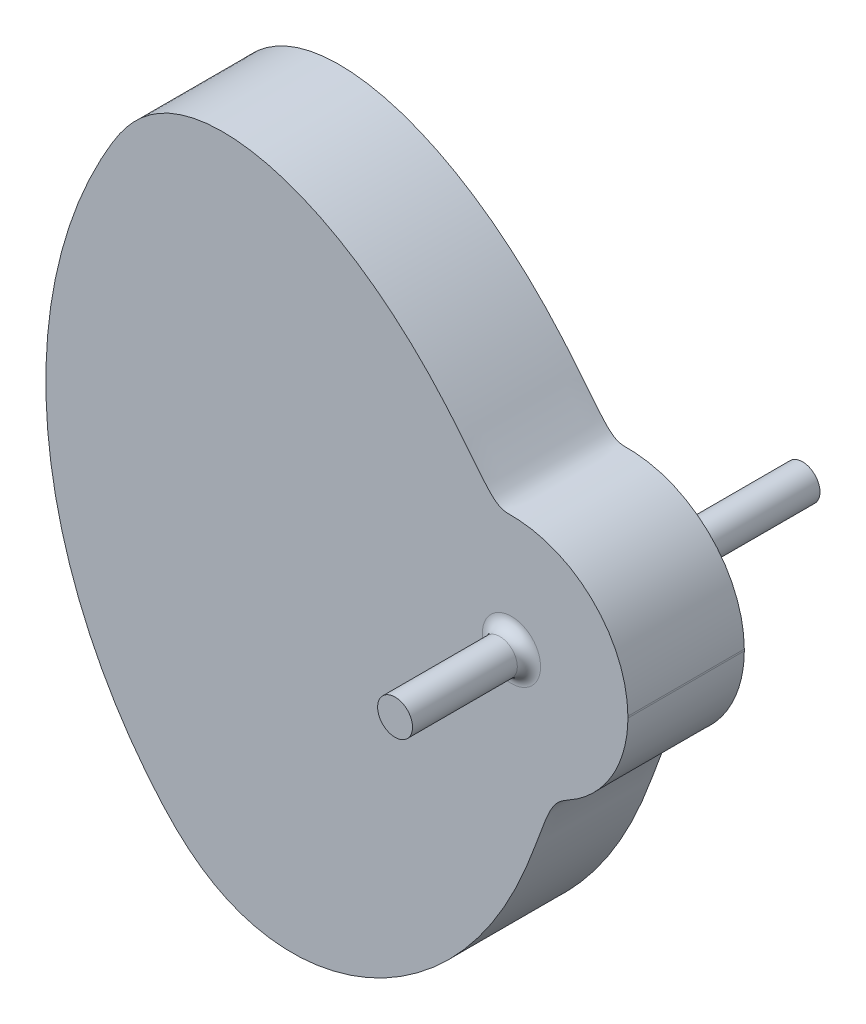
SolidWorks part; units mm, degrees
ref_plane "Front Plane" through (0, 0, 0) normal (0, 0, 1) x (1, 0, 0)
ref_plane "Top Plane" through (0, 0, 0) normal (0, 1, 0) x (1, 0, 0)
ref_plane "Right Plane" through (0, 0, 0) normal (1, 0, 0) x (0, 0, -1)
curve "Curve8"
  spline degree 3 poles (25.4, 0, 0) (25.3998, 0.0847, 0) (25.3993, 0.254, 0) (25.3953, 0.508, 0) (25.389, 0.7619, 0) (25.3801, 1.0157, 0) (25.3687, 1.2695, 0) (25.3547, 1.5231, 0) (25.3382, 1.7766, 0) (25.3192, 2.0299, 0) (25.2976, 2.283, 0) (25.2735, 2.5358, 0) (25.2469, 2.7884, 0) (25.2178, 3.0407, 0) (25.1861, 3.2928, 0) (25.1519, 3.5445, 0) (25.1152, 3.7958, 0) (25.076, 4.0467, 0) (25.0343, 4.2973, 0) (24.99, 4.5474, 0) (24.9433, 4.7971, 0) (24.8941, 5.0463, 0) (24.8424, 5.295, 0) (24.7882, 5.5431, 0) (24.7315, 5.7907, 0) (24.6724, 6.0377, 0) (24.6108, 6.2842, 0) (24.5467, 6.53, 0) (24.4802, 6.7751, 0) (24.4112, 7.0196, 0) (24.3398, 7.2633, 0) (24.266, 7.5063, 0) (24.1897, 7.7486, 0) (24.111, 7.9901, 0) (24.0299, 8.2308, 0) (23.9464, 8.4707, 0) (23.8605, 8.7097, 0) (23.7722, 8.9479, 0) (23.6815, 9.1852, 0) (23.5885, 9.4215, 0) (23.4931, 9.6569, 0) (23.3953, 9.8914, 0) (23.2953, 10.1248, 0) (23.1928, 10.3573, 0) (23.0881, 10.5887, 0) (22.9811, 10.819, 0) (22.8717, 11.0483, 0) (22.7601, 11.2765, 0) (22.6462, 11.5035, 0) (22.53, 11.7294, 0) (22.4116, 11.9541, 0) (22.291, 12.1776, 0) (22.1681, 12.3999, 0) (22.043, 12.621, 0) (21.9157, 12.8408, 0) (21.7862, 13.0593, 0) (21.6545, 13.2765, 0) (21.5206, 13.4924, 0) (21.3846, 13.7069, 0) (21.2465, 13.92, 0) (21.1062, 14.1318, 0) (20.9639, 14.3422, 0) (20.8194, 14.5511, 0) (20.6729, 14.7585, 0) (20.5242, 14.9645, 0) (20.3736, 15.169, 0) (20.2209, 15.372, 0) (20.0661, 15.5734, 0) (19.9094, 15.7733, 0) (19.7507, 15.9716, 0) (19.59, 16.1683, 0) (19.4273, 16.3634, 0) (19.2627, 16.5569, 0) (19.0962, 16.7486, 0) (18.9277, 16.9388, 0) (18.7574, 17.1272, 0) (18.5852, 17.3139, 0) (18.4111, 17.4989, 0) (18.2352, 17.6821, 0) (18.0575, 17.8636, 0) (17.878, 18.0433, 0) (17.6966, 18.2211, 0) (17.5136, 18.3972, 0) (17.3287, 18.5714, 0) (17.1421, 18.7438, 0) (16.9538, 18.9143, 0) (16.7639, 19.0828, 0) (16.5722, 19.2495, 0) (16.3789, 19.4143, 0) (16.1839, 19.5771, 0) (15.9873, 19.738, 0) (15.7892, 19.8968, 0) (15.5894, 20.0537, 0) (15.3881, 20.2086, 0) (15.1852, 20.3615, 0) (14.9809, 20.5123, 0) (14.775, 20.6611, 0) (14.5677, 20.8078, 0) (14.3588, 20.9524, 0) (14.1486, 21.095, 0) (13.937, 21.2354, 0) (13.7239, 21.3737, 0) (13.5095, 21.5099, 0) (13.2937, 21.6439, 0) (13.0766, 21.7758, 0) (12.8582, 21.9054, 0) (12.6385, 22.0329, 0) (12.4176, 22.1582, 0) (12.1954, 22.2813, 0) (11.9719, 22.4021, 0) (11.7473, 22.5207, 0) (11.5215, 22.637, 0) (11.2946, 22.7511, 0) (11.0665, 22.8629, 0) (10.8373, 22.9725, 0) (10.6071, 23.0797, 0) (10.3758, 23.1846, 0) (10.1434, 23.2872, 0) (9.91, 23.3875, 0) (9.6757, 23.4854, 0) (9.4403, 23.581, 0) (9.204, 23.6742, 0) (8.9668, 23.765, 0) (8.7287, 23.8535, 0) (8.4898, 23.9396, 0) (8.25, 24.0233, 0) (8.0093, 24.1046, 0) (7.7679, 24.1835, 0) (7.5257, 24.26, 0) (7.2827, 24.334, 0) (7.039, 24.4056, 0) (6.7946, 24.4748, 0) (6.5495, 24.5415, 0) (6.3038, 24.6058, 0) (6.0574, 24.6676, 0) (5.8104, 24.7269, 0) (5.5629, 24.7838, 0) (5.3148, 24.8382, 0) (5.0661, 24.8901, 0) (4.817, 24.9395, 0) (4.5673, 24.9864, 0) (4.3172, 25.0308, 0) (4.0667, 25.0728, 0) (3.8158, 25.1122, 0) (3.5645, 25.1491, 0) (3.3128, 25.1835, 0) (3.0608, 25.2153, 0) (2.8085, 25.2447, 0) (2.5559, 25.2715, 0) (2.3031, 25.2958, 0) (2.05, 25.3176, 0) (1.7968, 25.3368, 0) (1.5433, 25.3535, 0) (1.2897, 25.3677, 0) (1.036, 25.3793, 0) (0.7821, 25.3884, 0) (0.5282, 25.3949, 0) (0.2742, 25.3989, 0) (0.0982, 25.4, 0) (-0.0779, 25.4, 0) (-0.254, 25.3992, 0) (-0.5082, 25.3992, 0) (-0.7628, 25.4043, 0) (-1.0181, 25.4179, 0) (-1.2748, 25.4431, 0) (-1.5333, 25.4829, 0) (-1.7942, 25.5403, 0) (-2.0584, 25.6178, 0) (-2.3265, 25.7176, 0) (-2.5995, 25.8418, 0) (-2.8782, 25.9922, 0) (-3.1636, 26.1705, 0) (-3.457, 26.3779, 0) (-3.7593, 26.6159, 0) (-4.0719, 26.8853, 0) (-4.396, 27.187, 0) (-4.7327, 27.5217, 0) (-5.0833, 27.89, 0) (-5.449, 28.292, 0) (-5.831, 28.7281, 0) (-6.2306, 29.1981, 0) (-6.6488, 29.7019, 0) (-7.0868, 30.2392, 0) (-7.5457, 30.8095, 0) (-8.0266, 31.4122, 0) (-8.5304, 32.0464, 0) (-9.0582, 32.7113, 0) (-9.6107, 33.4058, 0) (-10.1889, 34.1289, 0) (-10.7934, 34.8791, 0) (-11.4251, 35.6552, 0) (-12.0844, 36.4557, 0) (-12.772, 37.279, 0) (-13.4884, 38.1234, 0) (-14.2338, 38.9872, 0) (-15.0087, 39.8685, 0) (-15.8131, 40.7655, 0) (-16.6474, 41.6762, 0) (-17.5114, 42.5986, 0) (-18.4052, 43.5307, 0) (-19.3286, 44.4704, 0) (-20.2813, 45.4154, 0) (-21.2631, 46.3638, 0) (-22.2735, 47.3132, 0) (-23.312, 48.2616, 0) (-24.378, 49.2067, 0) (-25.4708, 50.1462, 0) (-26.5897, 51.0781, 0) (-27.7337, 52.0001, 0) (-28.902, 52.9101, 0) (-30.0935, 53.8059, 0) (-31.307, 54.6853, 0) (-32.5415, 55.5464, 0) (-33.7956, 56.3871, 0) (-35.0679, 57.2054, 0) (-36.3572, 57.9993, 0) (-37.6619, 58.767, 0) (-38.9805, 59.5066, 0) (-40.3115, 60.2164, 0) (-41.6531, 60.8947, 0) (-43.0037, 61.54, 0) (-44.3617, 62.1506, 0) (-45.7252, 62.7251, 0) (-47.0924, 63.2622, 0) (-48.4616, 63.7607, 0) (-49.8308, 64.2193, 0) (-51.1984, 64.637, 0) (-52.5624, 65.0128, 0) (-53.9209, 65.3459, 0) (-55.2721, 65.6354, 0) (-56.6142, 65.8808, 0) (-57.9454, 66.0815, 0) (-59.2638, 66.2371, 0) (-60.5677, 66.3473, 0) (-61.8554, 66.4117, 0) (-63.1252, 66.4305, 0) (-64.3755, 66.4035, 0) (-65.6047, 66.3309, 0) (-66.8114, 66.2131, 0) (-67.9941, 66.0502, 0) (-69.1514, 65.8429, 0) (-70.2822, 65.5917, 0) (-71.3853, 65.2973, 0) (-72.4597, 64.9606, 0) (-73.5044, 64.5824, 0) (-74.5187, 64.1639, 0) (-75.5019, 63.706, 0) (-76.4534, 63.2101, 0) (-77.3729, 62.6775, 0) (-78.2602, 62.1097, 0) (-79.1152, 61.5081, 0) (-79.9381, 60.8743, 0) (-80.7291, 60.2101, 0) (-81.4888, 59.5171, 0) (-82.2178, 58.7973, 0) (-82.9171, 58.0524, 0) (-83.5877, 57.2844, 0) (-84.231, 56.4954, 0) (-84.8486, 55.6873, 0) (-85.4422, 54.8621, 0) (-86.014, 54.022, 0) (-86.5661, 53.1691, 0) (-87.1011, 52.3053, 0) (-87.5733, 51.5144, 0) (-88.0367, 50.7184, 0) (-88.4932, 49.9184, 0) (-88.988, 49.031, 0) (-89.4739, 48.1387, 0) (-89.9508, 47.2416, 0) (-90.4187, 46.3397, 0) (-90.8775, 45.4332, 0) (-91.3273, 44.5222, 0) (-91.768, 43.6067, 0) (-92.1994, 42.6869, 0) (-92.6217, 41.7627, 0) (-93.0347, 40.8345, 0) (-93.4384, 39.9021, 0) (-93.8327, 38.9657, 0) (-94.2177, 38.0255, 0) (-94.5932, 37.0814, 0) (-94.9593, 36.1336, 0) (-95.3159, 35.1822, 0) (-95.6629, 34.2273, 0) (-96.0004, 33.269, 0) (-96.3283, 32.3074, 0) (-96.6465, 31.3425, 0) (-96.9551, 30.3745, 0) (-97.254, 29.4034, 0) (-97.5432, 28.4294, 0) (-97.8226, 27.4526, 0) (-98.0922, 26.473, 0) (-98.352, 25.4908, 0) (-98.602, 24.506, 0) (-98.8422, 23.5188, 0) (-99.0724, 22.5292, 0) (-99.2927, 21.5373, 0) (-99.5031, 20.5434, 0) (-99.7036, 19.5473, 0) (-99.8941, 18.5493, 0) (-100.0746, 17.5495, 0) (-100.2451, 16.5479, 0) (-100.4055, 15.5446, 0) (-100.5559, 14.5398, 0) (-100.6963, 13.5335, 0) (-100.8266, 12.5259, 0) (-100.9468, 11.517, 0) (-101.057, 10.507, 0) (-101.157, 9.4959, 0) (-101.2469, 8.4839, 0) (-101.3266, 7.471, 0) (-101.3963, 6.4574, 0) (-101.4558, 5.4431, 0) (-101.5051, 4.4283, 0) (-101.5444, 3.4131, 0) (-101.5734, 2.3975, 0) (-101.5923, 1.3816, 0) (-101.601, 0.3656, 0) (-101.5996, -0.6504, 0) (-101.588, -1.6663, 0) (-101.5663, -2.6821, 0) (-101.5344, -3.6976, 0) (-101.4923, -4.7128, 0) (-101.4401, -5.7274, 0) (-101.3778, -6.7415, 0) (-101.3053, -7.7549, 0) (-101.2227, -8.7676, 0) (-101.13, -9.7794, 0) (-101.0271, -10.7902, 0) (-100.9142, -11.7999, 0) (-100.7911, -12.8084, 0) (-100.658, -13.8157, 0) (-100.5148, -14.8215, 0) (-100.3616, -15.8259, 0) (-100.1983, -16.8287, 0) (-100.025, -17.8299, 0) (-99.8417, -18.8292, 0) (-99.6484, -19.8267, 0) (-99.4452, -20.8221, 0) (-99.232, -21.8155, 0) (-99.0089, -22.8067, 0) (-98.7759, -23.7957, 0) (-98.533, -24.7822, 0) (-98.2802, -25.7663, 0) (-98.0176, -26.7478, 0) (-97.7453, -27.7266, 0) (-97.4631, -28.7027, 0) (-97.1712, -29.6758, 0) (-96.8696, -30.6461, 0) (-96.5583, -31.6132, 0) (-96.2374, -32.5772, 0) (-95.9068, -33.5379, 0) (-95.5666, -34.4953, 0) (-95.2169, -35.4492, 0) (-94.8576, -36.3996, 0) (-94.4889, -37.3463, 0) (-94.1107, -38.2894, 0) (-93.7231, -39.2285, 0) (-93.3262, -40.1638, 0) (-92.9199, -41.095, 0) (-92.5043, -42.0222, 0) (-92.0794, -42.9451, 0) (-91.6454, -43.8637, 0) (-91.2022, -44.778, 0) (-90.7499, -45.6877, 0) (-90.2884, -46.5929, 0) (-89.818, -47.4935, 0) (-89.3386, -48.3893, 0) (-88.8502, -49.2802, 0) (-88.353, -50.1662, 0) (-87.8469, -51.0472, 0) (-87.3321, -51.9231, 0) (-86.8085, -52.7938, 0) (-86.2762, -53.6593, 0) (-85.7353, -54.5193, 0) (-85.1859, -55.374, 0) (-84.6279, -56.223, 0) (-84.0614, -57.0665, 0) (-83.4866, -57.9042, 0) (-82.9033, -58.7362, 0) (-82.3118, -59.5623, 0) (-81.7121, -60.3824, 0) (-81.1042, -61.1965, 0) (-80.4882, -62.0045, 0) (-79.8642, -62.8062, 0) (-79.2321, -63.6017, 0) (-78.5921, -64.3908, 0) (-78.1229, -64.9578, 0) (-77.6503, -65.5219, 0) (-77.1744, -66.0833, 0) (-76.5085, -66.8507, 0) (-75.8326, -67.6092, 0) (-75.1456, -68.3577, 0) (-74.4467, -69.095, 0) (-73.7351, -69.82, 0) (-73.0101, -70.5316, 0) (-72.2711, -71.2286, 0) (-71.5175, -71.9099, 0) (-70.7489, -72.5745, 0) (-69.9649, -73.2213, 0) (-69.1653, -73.8492, 0) (-68.3497, -74.4571, 0) (-67.5182, -75.0442, 0) (-66.6705, -75.6094, 0) (-65.8067, -76.1519, 0) (-64.9269, -76.6706, 0) (-64.0312, -77.1648, 0) (-63.1197, -77.6335, 0) (-62.1928, -78.0761, 0) (-61.2507, -78.4917, 0) (-60.2938, -78.8796, 0) (-59.3225, -79.2392, 0) (-58.3373, -79.5698, 0) (-57.3386, -79.8709, 0) (-56.327, -80.1418, 0) (-55.3031, -80.3822, 0) (-54.2676, -80.5915, 0) (-53.221, -80.7694, 0) (-52.1641, -80.9154, 0) (-51.0976, -81.0294, 0) (-50.0222, -81.1109, 0) (-48.9388, -81.1599, 0) (-47.8481, -81.1761, 0) (-46.751, -81.1595, 0) (-45.6482, -81.11, 0) (-44.5407, -81.0275, 0) (-43.4293, -80.9121, 0) (-42.3148, -80.7639, 0) (-41.1983, -80.583, 0) (-40.0804, -80.3696, 0) (-38.9623, -80.1239, 0) (-37.8447, -79.8462, 0) (-36.7285, -79.5368, 0) (-35.6147, -79.196, 0) (-34.5042, -78.8244, 0) (-33.3977, -78.4222, 0) (-32.2962, -77.9901, 0) (-31.2006, -77.5286, 0) (-30.1117, -77.0382, 0) (-29.0303, -76.5195, 0) (-27.9573, -75.9733, 0) (-26.8935, -75.4002, 0) (-25.8396, -74.8009, 0) (-24.7964, -74.1762, 0) (-23.7647, -73.527, 0) (-22.7452, -72.854, 0) (-21.7386, -72.1581, 0) (-20.7454, -71.4402, 0) (-19.7665, -70.7012, 0) (-18.8024, -69.9421, 0) (-17.8536, -69.1638, 0) (-16.9207, -68.3673, 0) (-16.0043, -67.5537, 0) (-15.1048, -66.724, 0) (-14.2227, -65.8792, 0) (-13.3583, -65.0205, 0) (-12.5121, -64.1488, 0) (-11.6845, -63.2653, 0) (-10.8756, -62.3711, 0) (-10.0859, -61.4673, 0) (-9.3154, -60.5551, 0) (-8.5646, -59.6355, 0) (-7.8334, -58.7097, 0) (-7.122, -57.7788, 0) (-6.4305, -56.8439, 0) (-5.759, -55.9063, 0) (-5.1074, -54.9669, 0) (-4.4758, -54.0269, 0) (-3.864, -53.0875, 0) (-3.272, -52.1497, 0) (-2.6996, -51.2146, 0) (-2.1467, -50.2833, 0) (-1.613, -49.3568, 0) (-1.0984, -48.4361, 0) (-0.6024, -47.5224, 0) (-0.1249, -46.6165, 0) (0.3345, -45.7194, 0) (0.7762, -44.8322, 0) (1.2007, -43.9557, 0) (1.6082, -43.0907, 0) (1.9994, -42.2382, 0) (2.3746, -41.399, 0) (2.7344, -40.5739, 0) (3.0793, -39.7636, 0) (3.4099, -38.9688, 0) (3.7267, -38.1903, 0) (4.0304, -37.4287, 0) (4.3216, -36.6846, 0) (4.6009, -35.9584, 0) (4.8689, -35.2509, 0) (5.1263, -34.5623, 0) (5.3737, -33.8932, 0) (5.6119, -33.2439, 0) (5.8415, -32.6148, 0) (6.0632, -32.0061, 0) (6.2776, -31.418, 0) (6.4855, -30.8508, 0) (6.6876, -30.3045, 0) (6.8845, -29.7793, 0) (7.0768, -29.2751, 0) (7.2653, -28.7918, 0) (7.4506, -28.3295, 0) (7.6332, -27.888, 0) (7.8139, -27.4671, 0) (7.9933, -27.0664, 0) (8.1718, -26.6858, 0) (8.35, -26.3248, 0) (8.5285, -25.9831, 0) (8.7077, -25.66, 0) (8.8881, -25.3553, 0) (9.0701, -25.0681, 0) (9.254, -24.798, 0) (9.4403, -24.5442, 0) (9.6291, -24.3061, 0) (9.8207, -24.0827, 0) (10.0154, -23.8733, 0) (10.2131, -23.677, 0) (10.414, -23.4928, 0) (10.618, -23.3198, 0) (10.8251, -23.1569, 0) (11.0352, -23.003, 0) (11.248, -22.857, 0) (11.4632, -22.7176, 0) (11.6807, -22.5837, 0) (11.8998, -22.454, 0) (12.1201, -22.3271, 0) (12.3411, -22.2017, 0) (12.5346, -22.092, 0) (12.7275, -21.9815, 0) (12.9195, -21.8693, 0) (13.1376, -21.739, 0) (13.3543, -21.6066, 0) (13.5697, -21.4719, 0) (13.7838, -21.3352, 0) (13.9964, -21.1963, 0) (14.2077, -21.0553, 0) (14.4175, -20.9121, 0) (14.6259, -20.7669, 0) (14.8328, -20.6196, 0) (15.0383, -20.4703, 0) (15.2422, -20.3189, 0) (15.4447, -20.1654, 0) (15.6455, -20.01, 0) (15.8449, -19.8525, 0) (16.0426, -19.6931, 0) (16.2387, -19.5317, 0) (16.4332, -19.3683, 0) (16.6261, -19.203, 0) (16.8173, -19.0358, 0) (17.0068, -18.8667, 0) (17.1946, -18.6957, 0) (17.3807, -18.5228, 0) (17.565, -18.348, 0) (17.7476, -18.1715, 0) (17.9285, -17.9931, 0) (18.1075, -17.8129, 0) (18.2847, -17.631, 0) (18.4601, -17.4472, 0) (18.6337, -17.2618, 0) (18.8053, -17.0746, 0) (18.9751, -16.8857, 0) (19.143, -16.6951, 0) (19.309, -16.5028, 0) (19.4731, -16.3089, 0) (19.6352, -16.1134, 0) (19.7954, -15.9162, 0) (19.9535, -15.7175, 0) (20.1097, -15.5171, 0) (20.2639, -15.3153, 0) (20.416, -15.1119, 0) (20.5661, -14.9069, 0) (20.7141, -14.7005, 0) (20.8601, -14.4927, 0) (21.004, -14.2834, 0) (21.1458, -14.0726, 0) (21.2854, -13.8604, 0) (21.423, -13.6469, 0) (21.5584, -13.432, 0) (21.6916, -13.2157, 0) (21.8227, -12.9982, 0) (21.9516, -12.7793, 0) (22.0783, -12.5591, 0) (22.2027, -12.3377, 0) (22.325, -12.1151, 0) (22.445, -11.8912, 0) (22.5628, -11.6662, 0) (22.6784, -11.44, 0) (22.7916, -11.2126, 0) (22.9026, -10.9842, 0) (23.0113, -10.7546, 0) (23.1177, -10.524, 0) (23.2218, -10.2923, 0) (23.3235, -10.0595, 0) (23.423, -9.8258, 0) (23.5201, -9.5911, 0) (23.6148, -9.3554, 0) (23.7072, -9.1188, 0) (23.7972, -8.8813, 0) (23.8848, -8.6428, 0) (23.97, -8.4036, 0) (24.0528, -8.1635, 0) (24.1333, -7.9225, 0) (24.2113, -7.6808, 0) (24.2869, -7.4383, 0) (24.3601, -7.1951, 0) (24.4308, -6.9511, 0) (24.4991, -6.7065, 0) (24.5649, -6.4611, 0) (24.6283, -6.2152, 0) (24.6892, -5.9686, 0) (24.7477, -5.7214, 0) (24.8036, -5.4736, 0) (24.8571, -5.2253, 0) (24.9082, -4.9765, 0) (24.9567, -4.7272, 0) (25.0027, -4.4774, 0) (25.0462, -4.2271, 0) (25.0872, -3.9765, 0) (25.1257, -3.7254, 0) (25.1617, -3.474, 0) (25.1952, -3.2222, 0) (25.2262, -2.9701, 0) (25.2546, -2.7177, 0) (25.2805, -2.465, 0) (25.3039, -2.212, 0) (25.3248, -1.9589, 0) (25.3431, -1.7056, 0) (25.3589, -1.452, 0) (25.3721, -1.1984, 0) (25.3829, -0.9446, 0) (25.391, -0.6907, 0) (25.3968, -0.4368, 0) (25.3985, -0.2675, 0) (25.3993, -0.1828, 0) knots 0 0 0 0 0.000598 0.001196 0.001794 0.002392 0.00299 0.003589 0.004187 0.004785 0.005383 0.005981 0.006579 0.007177 0.007775 0.008373 0.008971 0.009569 0.010167 0.010766 0.011364 0.011962 0.01256 0.013158 0.013756 0.014354 0.014952 0.01555 0.016148 0.016746 0.017344 0.017943 0.018541 0.019139 0.019737 0.020335 0.020933 0.021531 0.022129 0.022727 0.023325 0.023923 0.024521 0.02512 0.025718 0.026316 0.026914 0.027512 0.02811 0.028708 0.029306 0.029904 0.030502 0.0311 0.031698 0.032297 0.032895 0.033493 0.034091 0.034689 0.035287 0.035885 0.036483 0.037081 0.037679 0.038277 0.038875 0.039474 0.040072 0.04067 0.041268 0.041866 0.042464 0.043062 0.04366 0.044258 0.044856 0.045454 0.046052 0.046651 0.047249 0.047847 0.048445 0.049043 0.049641 0.050239 0.050837 0.051435 0.052033 0.052631 0.053229 0.053828 0.054426 0.055024 0.055622 0.05622 0.056818 0.057416 0.058014 0.058612 0.05921 0.059808 0.060406 0.061005 0.061603 0.062201 0.062799 0.063397 0.063995 0.064593 0.065191 0.065789 0.066387 0.066985 0.067583 0.068182 0.06878 0.069378 0.069976 0.070574 0.071172 0.07177 0.072368 0.072966 0.073564 0.074162 0.07476 0.075359 0.075957 0.076555 0.077153 0.077751 0.078349 0.078947 0.079545 0.080143 0.080741 0.081339 0.081937 0.082536 0.083134 0.083732 0.08433 0.084928 0.085526 0.086124 0.086722 0.08732 0.087918 0.088516 0.089114 0.089713 0.090311 0.090909 0.091507 0.092105 0.092703 0.093301 0.093899 0.093947 0.094545 0.095143 0.095742 0.096343 0.096949 0.097563 0.09819 0.098835 0.099506 0.100209 0.100952 0.101742 0.102585 0.103489 0.104458 0.105499 0.106616 0.107812 0.109091 0.110455 0.111907 0.113448 0.11508 0.116804 0.118619 0.120526 0.122525 0.124616 0.126796 0.129065 0.131422 0.133864 0.136391 0.138999 0.141686 0.144451 0.147289 0.150198 0.153175 0.156217 0.15932 0.162481 0.165696 0.168962 0.172275 0.17563 0.179025 0.182455 0.185916 0.189404 0.192915 0.196445 0.19999 0.203547 0.20711 0.210676 0.214242 0.217803 0.221355 0.224896 0.228421 0.231928 0.235413 0.238872 0.242304 0.245704 0.249072 0.252403 0.255697 0.258951 0.262164 0.265333 0.268459 0.27154 0.274575 0.277565 0.280509 0.283408 0.286261 0.289071 0.291839 0.294565 0.297252 0.299901 0.302516 0.305098 0.30765 0.310174 0.312675 0.315154 0.317614 0.320058 0.322488 0.324908 0.327319 0.329724 0.332123 0.33452 0.336914 0.339307 0.341699 0.344092 0.346484 0.348876 0.350598 0.35299 0.355383 0.357775 0.360167 0.36256 0.364952 0.367344 0.369737 0.372129 0.374521 0.376914 0.379306 0.381698 0.384091 0.386483 0.388875 0.391268 0.39366 0.396052 0.398445 0.400837 0.403229 0.405622 0.408014 0.410406 0.412799 0.415191 0.417584 0.419976 0.422368 0.424761 0.427153 0.429545 0.431938 0.43433 0.436722 0.439115 0.441507 0.443899 0.446292 0.448684 0.451076 0.453469 0.455861 0.458253 0.460646 0.463038 0.46543 0.467823 0.470215 0.472607 0.475 0.477392 0.479784 0.482177 0.484569 0.486961 0.489354 0.491746 0.494138 0.496531 0.498923 0.501315 0.503708 0.5061 0.508492 0.510885 0.513277 0.515669 0.518062 0.520454 0.522846 0.525239 0.527631 0.530023 0.532416 0.534808 0.5372 0.539593 0.541985 0.544377 0.54677 0.549162 0.551554 0.553947 0.556339 0.558731 0.561124 0.563516 0.565908 0.568301 0.570693 0.573085 0.575478 0.57787 0.580262 0.582655 0.585047 0.587439 0.589832 0.592224 0.594616 0.597009 0.599401 0.601793 0.604186 0.606578 0.60897 0.611363 0.613755 0.616147 0.61854 0.620932 0.623324 0.625717 0.628109 0.630501 0.632894 0.635286 0.637678 0.640071 0.642463 0.642877 0.645269 0.647662 0.650054 0.652446 0.654838 0.65723 0.659622 0.662014 0.664405 0.666798 0.669191 0.671584 0.673979 0.676375 0.678774 0.681175 0.68358 0.685988 0.688401 0.690819 0.693243 0.695673 0.698111 0.700558 0.703013 0.705478 0.707954 0.710441 0.71294 0.715452 0.717977 0.720516 0.723069 0.725637 0.72822 0.730819 0.733434 0.736064 0.738711 0.741374 0.744054 0.746749 0.74946 0.752187 0.75493 0.757687 0.760459 0.763245 0.766045 0.768857 0.771681 0.774516 0.777361 0.780216 0.783079 0.78595 0.788826 0.791708 0.794594 0.797482 0.800372 0.803261 0.80615 0.809036 0.811918 0.814794 0.817663 0.820524 0.823375 0.826215 0.829041 0.831853 0.834649 0.837427 0.840186 0.842925 0.845641 0.848333 0.851 0.85364 0.856252 0.858834 0.861385 0.863903 0.866387 0.868835 0.871247 0.873621 0.875955 0.878248 0.8805 0.882709 0.884874 0.886994 0.889067 0.891095 0.893074 0.895005 0.896887 0.898719 0.9005 0.902231 0.903911 0.90554 0.907117 0.908642 0.910116 0.911538 0.91291 0.91423 0.915501 0.916722 0.917894 0.919019 0.920097 0.92113 0.922119 0.923067 0.923974 0.924843 0.925676 0.926475 0.927244 0.927984 0.928699 0.92939 0.930062 0.930717 0.931358 0.931987 0.932607 0.933219 0.933826 0.93443 0.93503 0.93563 0.936228 0.936827 0.937425 0.937799 0.938397 0.938995 0.939594 0.940192 0.94079 0.941388 0.941986 0.942584 0.943182 0.94378 0.944378 0.944976 0.945574 0.946172 0.946771 0.947369 0.947967 0.948565 0.949163 0.949761 0.950359 0.950957 0.951555 0.952153 0.952751 0.953349 0.953948 0.954546 0.955144 0.955742 0.95634 0.956938 0.957536 0.958134 0.958732 0.95933 0.959928 0.960526 0.961125 0.961723 0.962321 0.962919 0.963517 0.964115 0.964713 0.965311 0.965909 0.966507 0.967105 0.967703 0.968302 0.9689 0.969498 0.970096 0.970694 0.971292 0.97189 0.972488 0.973086 0.973684 0.974282 0.97488 0.975479 0.976077 0.976675 0.977273 0.977871 0.978469 0.979067 0.979665 0.980263 0.980861 0.981459 0.982057 0.982656 0.983254 0.983852 0.98445 0.985048 0.985646 0.986244 0.986842 0.98744 0.988038 0.988636 0.989234 0.989833 0.990431 0.991029 0.991627 0.992225 0.992823 0.993421 0.994019 0.994617 0.995215 0.995813 0.996411 0.99701 0.997608 0.998206 0.998804 0.999402 1 1 1 1
sketch "Sketch1" plane through (0, 0, 0) normal (0, 0, 1) x (1, 0, 0)
  line L0 (25.3993, 0.1711) -> (25.3993, -0.1828)
  spline S0 degree 3 poles (3024.3671, -21.4196) (8.5864, -30.0959) (25.6331, -14.7682) (25.3953, 0.508) (25.389, 0.7619) (25.3742, 1.185) (25.323, 2.115) (25.1898, 3.3788) (24.9394, 4.8826) (24.6251, 6.2878) (24.2038, 7.7531) (23.6953, 9.1905) (23.1016, 10.5949) (22.4247, 11.9611) (21.6671, 13.2842) (20.8316, 14.5596) (19.9716, 15.7146) (19.1038, 16.7554) (18.1851, 17.7515) (17.1521, 18.7547) (15.9967, 19.7495) (14.7836, 20.6732) (13.5174, 21.5224) (12.2025, 22.2943) (10.8437, 22.9859) (9.4458, 23.5947) (8.014, 24.1187) (6.5533, 24.5558) (5.1515, 24.8852) (3.7339, 25.137) (2.3044, 25.3106) (1.1208, 25.3826) (0.3522, 25.3986) (0.0067, 25.4005) (-0.254, 25.3992) (-0.5082, 25.3992) (-0.7628, 25.4043) (-1.0181, 25.4179) (-1.2748, 25.4431) (-1.5333, 25.4829) (-1.7942, 25.5403) (-2.0584, 25.6178) (-2.3265, 25.7176) (-2.5995, 25.8418) (-2.8782, 25.9922) (-3.1636, 26.1705) (-3.457, 26.3779) (-3.7593, 26.6159) (-4.0719, 26.8853) (-4.396, 27.187) (-4.7327, 27.5217) (-5.0833, 27.89) (-5.449, 28.292) (-5.831, 28.7281) (-6.2306, 29.1981) (-6.6488, 29.7019) (-7.0868, 30.2392) (-7.5457, 30.8095) (-8.0266, 31.4122) (-8.5304, 32.0464) (-9.0582, 32.7113) (-9.6107, 33.4058) (-10.1889, 34.1289) (-10.7934, 34.8791) (-11.4251, 35.6552) (-12.0844, 36.4557) (-12.772, 37.279) (-13.4884, 38.1234) (-14.2338, 38.9872) (-15.0087, 39.8685) (-15.8131, 40.7655) (-16.6474, 41.6762) (-17.5114, 42.5986) (-18.4052, 43.5307) (-19.6476, 44.795) (-21.2721, 46.3855) (-23.3186, 48.2815) (-25.1058, 49.8422) (-26.9691, 51.3942) (-28.5104, 52.6157) (-30.0935, 53.8059) (-31.307, 54.6853) (-32.5415, 55.5464) (-33.7956, 56.3871) (-35.0679, 57.2054) (-36.3572, 57.9993) (-37.6619, 58.767) (-38.9805, 59.5066) (-40.3115, 60.2164) (-41.6531, 60.8947) (-43.0037, 61.54) (-44.3617, 62.1506) (-45.7252, 62.7251) (-47.0924, 63.2622) (-48.4616, 63.7607) (-49.8308, 64.2193) (-51.1984, 64.637) (-52.5624, 65.0128) (-53.9209, 65.3459) (-55.2721, 65.6354) (-56.6142, 65.8808) (-57.9454, 66.0815) (-59.2638, 66.2371) (-60.5677, 66.3473) (-61.8554, 66.4117) (-63.1252, 66.4305) (-64.3755, 66.4035) (-65.6047, 66.3309) (-66.8114, 66.2131) (-67.9941, 66.0502) (-69.1514, 65.8429) (-70.2822, 65.5917) (-71.3853, 65.2973) (-72.4597, 64.9606) (-73.5044, 64.5824) (-74.5187, 64.1639) (-75.5019, 63.706) (-76.4534, 63.2101) (-77.3729, 62.6775) (-78.2602, 62.1097) (-79.1152, 61.5081) (-79.9381, 60.8743) (-80.7291, 60.2101) (-81.4888, 59.5171) (-82.2178, 58.7973) (-82.9171, 58.0524) (-83.5877, 57.2844) (-84.231, 56.4954) (-84.8486, 55.6873) (-85.4422, 54.8621) (-86.014, 54.022) (-86.5661, 53.1691) (-87.1011, 52.3053) (-87.5733, 51.5144) (-88.7182, 49.5477) (-90.2928, 46.6558) (-92.2225, 42.6975) (-93.8562, 38.9755) (-95.3397, 35.191) (-96.6707, 31.3503) (-97.8471, 27.4594) (-98.8669, 23.5246) (-99.7285, 19.5522) (-100.4306, 15.5485) (-100.9721, 11.5199) (-101.352, 7.4729) (-101.5697, 3.4139) (-101.625, -0.6505) (-101.5177, -4.7139) (-101.248, -8.7698) (-100.8163, -12.8116) (-100.2233, -16.8329) (-99.47, -20.8273) (-98.5576, -24.7884) (-97.4875, -28.7098) (-96.2614, -32.5853) (-94.8814, -36.4087) (-93.3495, -40.1738) (-91.6683, -43.8747) (-89.8405, -47.5053) (-87.8689, -51.06) (-85.7568, -54.533) (-83.5074, -57.9187) (-81.3231, -60.9374) (-79.6588, -63.0756) (-78.5921, -64.3908) (-78.1229, -64.9578) (-77.6503, -65.5219) (-77.1744, -66.0833) (-76.5085, -66.8507) (-75.8326, -67.6092) (-75.1456, -68.3577) (-74.4467, -69.095) (-73.7351, -69.82) (-73.0101, -70.5316) (-72.2711, -71.2286) (-71.5175, -71.9099) (-70.7489, -72.5745) (-69.9649, -73.2213) (-69.1653, -73.8492) (-68.3497, -74.4571) (-67.5182, -75.0442) (-66.6705, -75.6094) (-65.8067, -76.1519) (-64.9269, -76.6706) (-64.0312, -77.1648) (-63.1197, -77.6335) (-62.1928, -78.0761) (-61.2507, -78.4917) (-60.2938, -78.8796) (-59.3225, -79.2392) (-58.3373, -79.5698) (-57.3386, -79.8709) (-56.327, -80.1418) (-55.3031, -80.3822) (-54.2676, -80.5915) (-53.221, -80.7694) (-52.1641, -80.9154) (-51.0976, -81.0294) (-50.0222, -81.1109) (-48.9388, -81.1599) (-47.8481, -81.1761) (-46.751, -81.1595) (-45.6482, -81.11) (-44.5407, -81.0275) (-43.4293, -80.9121) (-42.3148, -80.7639) (-41.1983, -80.583) (-40.0804, -80.3696) (-38.9623, -80.1239) (-37.8447, -79.8462) (-36.7285, -79.5368) (-35.6147, -79.196) (-34.5042, -78.8244) (-33.3977, -78.4222) (-32.2962, -77.9901) (-31.2006, -77.5286) (-30.1117, -77.0382) (-29.0303, -76.5195) (-27.9573, -75.9733) (-26.8935, -75.4002) (-25.8396, -74.8009) (-24.7964, -74.1762) (-23.7647, -73.527) (-22.7452, -72.854) (-21.4022, -71.9255) (-20.0875, -70.9539) (-18.4811, -69.6891) (-16.9138, -68.377) (-15.0987, -66.7339) (-13.353, -65.0308) (-11.68, -63.276) (-10.0822, -61.4786) (-8.5617, -59.6473) (-7.12, -57.7913) (-5.7577, -55.9195) (-4.4753, -54.0409) (-3.2722, -52.1645) (-2.1476, -50.2988) (-1.0999, -48.4525) (-0.1271, -46.6336) (0.6298, -45.1346) (1.2007, -43.9557) (1.6082, -43.0907) (1.9994, -42.2382) (2.3746, -41.399) (2.7344, -40.5739) (3.0793, -39.7636) (3.4099, -38.9688) (3.7267, -38.1903) (4.0304, -37.4287) (4.3216, -36.6846) (4.6009, -35.9584) (4.8689, -35.2509) (5.1263, -34.5623) (5.3737, -33.8932) (5.6119, -33.2439) (5.8415, -32.6148) (6.0632, -32.0061) (6.2776, -31.418) (6.4855, -30.8508) (6.6876, -30.3045) (6.8845, -29.7793) (7.0768, -29.2751) (7.2653, -28.7918) (7.4506, -28.3295) (7.6332, -27.888) (7.8139, -27.4671) (7.9933, -27.0664) (8.1718, -26.6858) (8.35, -26.3248) (8.5285, -25.9831) (8.7077, -25.66) (8.8881, -25.3553) (9.0701, -25.0681) (9.254, -24.798) (9.4403, -24.5442) (9.6291, -24.3061) (9.8207, -24.0827) (10.0154, -23.8733) (10.2131, -23.677) (10.414, -23.4928) (10.618, -23.3198) (10.8251, -23.1569) (11.0352, -23.003) (11.248, -22.857) (11.4632, -22.7176) (11.6807, -22.5837) (11.8998, -22.454) (12.1201, -22.3271) (12.3411, -22.2017) (12.5346, -22.092) (13.0948, -21.7709) (14.0046, -21.2086) (15.2511, -20.3307) (16.4428, -19.3796) (17.5124, -18.4155) (18.5272, -17.3941) (19.4845, -16.3184) (20.4279, -15.1207) (21.2979, -13.8685) (22.0911, -12.5665) (22.8049, -11.2192) (23.4366, -9.8315) (23.984, -8.4085) (24.445, -6.9552) (24.8181, -5.4768) (25.1019, -3.9788) (25.263, -2.7185) (25.3326, -1.8746) (25.3589, -1.452) (25.3721, -1.1984) (25.3829, -0.9446) (25.391, -0.6907) (25.7388, 14.5832) (8.8024, 30.0333) (3024.508, -0.3506) knots -0.106127 -0.106127 -0.106127 -0.106127 0.000598 0.001196 0.001794 0.002392 0.004187 0.008373 0.011364 0.014952 0.018541 0.022129 0.025718 0.029306 0.032895 0.036483 0.040072 0.043062 0.046052 0.049641 0.053229 0.056818 0.060406 0.063995 0.067583 0.071172 0.07476 0.078349 0.081937 0.084928 0.088516 0.092105 0.093301 0.093947 0.094545 0.095143 0.095742 0.096343 0.096949 0.097563 0.09819 0.098835 0.099506 0.100209 0.100952 0.101742 0.102585 0.103489 0.104458 0.105499 0.106616 0.107812 0.109091 0.110455 0.111907 0.113448 0.11508 0.116804 0.118619 0.120526 0.122525 0.124616 0.126796 0.129065 0.131422 0.133864 0.136391 0.138999 0.141686 0.144451 0.147289 0.150198 0.153175 0.156217 0.15932 0.165696 0.172275 0.179025 0.182455 0.189404 0.192915 0.196445 0.19999 0.203547 0.20711 0.210676 0.214242 0.217803 0.221355 0.224896 0.228421 0.231928 0.235413 0.238872 0.242304 0.245704 0.249072 0.252403 0.255697 0.258951 0.262164 0.265333 0.268459 0.27154 0.274575 0.277565 0.280509 0.283408 0.286261 0.289071 0.291839 0.294565 0.297252 0.299901 0.302516 0.305098 0.30765 0.310174 0.312675 0.315154 0.317614 0.320058 0.322488 0.324908 0.327319 0.329724 0.332123 0.33452 0.336914 0.339307 0.341699 0.344092 0.346484 0.348876 0.350598 0.36256 0.372129 0.381698 0.391268 0.400837 0.410406 0.419976 0.429545 0.439115 0.448684 0.458253 0.467823 0.477392 0.486961 0.496531 0.5061 0.515669 0.525239 0.534808 0.544377 0.553947 0.563516 0.573085 0.582655 0.592224 0.601793 0.611363 0.620932 0.630501 0.637678 0.640071 0.642463 0.642877 0.645269 0.647662 0.650054 0.652446 0.654838 0.65723 0.659622 0.662014 0.664405 0.666798 0.669191 0.671584 0.673979 0.676375 0.678774 0.681175 0.68358 0.685988 0.688401 0.690819 0.693243 0.695673 0.698111 0.700558 0.703013 0.705478 0.707954 0.710441 0.71294 0.715452 0.717977 0.720516 0.723069 0.725637 0.72822 0.730819 0.733434 0.736064 0.738711 0.741374 0.744054 0.746749 0.74946 0.752187 0.75493 0.757687 0.760459 0.763245 0.766045 0.768857 0.771681 0.774516 0.777361 0.780216 0.783079 0.78595 0.788826 0.791708 0.797482 0.800372 0.80615 0.811918 0.817663 0.823375 0.829041 0.834649 0.840186 0.845641 0.851 0.856252 0.861385 0.866387 0.871247 0.875955 0.878248 0.8805 0.882709 0.884874 0.886994 0.889067 0.891095 0.893074 0.895005 0.896887 0.898719 0.9005 0.902231 0.903911 0.90554 0.907117 0.908642 0.910116 0.911538 0.91291 0.91423 0.915501 0.916722 0.917894 0.919019 0.920097 0.92113 0.922119 0.923067 0.923974 0.924843 0.925676 0.926475 0.927244 0.927984 0.928699 0.92939 0.930062 0.930717 0.931358 0.931987 0.932607 0.933219 0.933826 0.93443 0.93503 0.93563 0.936228 0.936827 0.937425 0.937799 0.941388 0.944976 0.948565 0.952153 0.955144 0.958732 0.962321 0.965909 0.969498 0.973086 0.976675 0.980263 0.983852 0.98744 0.991029 0.994617 0.996411 0.99701 0.997608 0.998206 0.998804 0.999402 1.106126 1.106126 1.106126 1.106126 only from (25.4, 0) to (25.3993, -0.1828) construction
  spline S1 degree 3 poles (25.3993, 0.1711) (25.3992, 0.1987) (25.3984, 0.311) (25.3953, 0.508) (25.389, 0.7619) (25.3742, 1.185) (25.323, 2.115) (25.1898, 3.3788) (24.9394, 4.8826) (24.6251, 6.2878) (24.2038, 7.7531) (23.6953, 9.1905) (23.1016, 10.5949) (22.4247, 11.9611) (21.6671, 13.2842) (20.8316, 14.5596) (19.9716, 15.7146) (19.1038, 16.7554) (18.1851, 17.7515) (17.1521, 18.7547) (15.9967, 19.7495) (14.7836, 20.6732) (13.5174, 21.5224) (12.2025, 22.2943) (10.8437, 22.9859) (9.4458, 23.5947) (8.014, 24.1187) (6.5533, 24.5558) (5.1515, 24.8852) (3.7339, 25.137) (2.3044, 25.3106) (1.1208, 25.3826) (0.3522, 25.3986) (0.0067, 25.4005) (-0.254, 25.3992) (-0.5082, 25.3992) (-0.7628, 25.4043) (-1.0181, 25.4179) (-1.2748, 25.4431) (-1.5333, 25.4829) (-1.7942, 25.5403) (-2.0584, 25.6178) (-2.3265, 25.7176) (-2.5995, 25.8418) (-2.8782, 25.9922) (-3.1636, 26.1705) (-3.457, 26.3779) (-3.7593, 26.6159) (-4.0719, 26.8853) (-4.396, 27.187) (-4.7327, 27.5217) (-5.0833, 27.89) (-5.449, 28.292) (-5.831, 28.7281) (-6.2306, 29.1981) (-6.6488, 29.7019) (-7.0868, 30.2392) (-7.5457, 30.8095) (-8.0266, 31.4122) (-8.5304, 32.0464) (-9.0582, 32.7113) (-9.6107, 33.4058) (-10.1889, 34.1289) (-10.7934, 34.8791) (-11.4251, 35.6552) (-12.0844, 36.4557) (-12.772, 37.279) (-13.4884, 38.1234) (-14.2338, 38.9872) (-15.0087, 39.8685) (-15.8131, 40.7655) (-16.6474, 41.6762) (-17.5114, 42.5986) (-18.4052, 43.5307) (-19.6476, 44.795) (-21.2721, 46.3855) (-23.3186, 48.2815) (-25.1058, 49.8422) (-26.9691, 51.3942) (-28.5104, 52.6157) (-30.0935, 53.8059) (-31.307, 54.6853) (-32.5415, 55.5464) (-33.7956, 56.3871) (-35.0679, 57.2054) (-36.3572, 57.9993) (-37.6619, 58.767) (-38.9805, 59.5066) (-40.3115, 60.2164) (-41.6531, 60.8947) (-43.0037, 61.54) (-44.3617, 62.1506) (-45.7252, 62.7251) (-47.0924, 63.2622) (-48.4616, 63.7607) (-49.8308, 64.2193) (-51.1984, 64.637) (-52.5624, 65.0128) (-53.9209, 65.3459) (-55.2721, 65.6354) (-56.6142, 65.8808) (-57.9454, 66.0815) (-59.2638, 66.2371) (-60.5677, 66.3473) (-61.8554, 66.4117) (-63.1252, 66.4305) (-64.3755, 66.4035) (-65.6047, 66.3309) (-66.8114, 66.2131) (-67.9941, 66.0502) (-69.1514, 65.8429) (-70.2822, 65.5917) (-71.3853, 65.2973) (-72.4597, 64.9606) (-73.5044, 64.5824) (-74.5187, 64.1639) (-75.5019, 63.706) (-76.4534, 63.2101) (-77.3729, 62.6775) (-78.2602, 62.1097) (-79.1152, 61.5081) (-79.9381, 60.8743) (-80.7291, 60.2101) (-81.4888, 59.5171) (-82.2178, 58.7973) (-82.9171, 58.0524) (-83.5877, 57.2844) (-84.231, 56.4954) (-84.8486, 55.6873) (-85.4422, 54.8621) (-86.014, 54.022) (-86.5661, 53.1691) (-87.1011, 52.3053) (-87.5733, 51.5144) (-88.7182, 49.5477) (-90.2928, 46.6558) (-92.2225, 42.6975) (-93.8562, 38.9755) (-95.3397, 35.191) (-96.6707, 31.3503) (-97.8471, 27.4594) (-98.8669, 23.5246) (-99.7285, 19.5522) (-100.4306, 15.5485) (-100.9721, 11.5199) (-101.352, 7.4729) (-101.5697, 3.4139) (-101.625, -0.6505) (-101.5177, -4.7139) (-101.248, -8.7698) (-100.8163, -12.8116) (-100.2233, -16.8329) (-99.47, -20.8273) (-98.5576, -24.7884) (-97.4875, -28.7098) (-96.2614, -32.5853) (-94.8814, -36.4087) (-93.3495, -40.1738) (-91.6683, -43.8747) (-89.8405, -47.5053) (-87.8689, -51.06) (-85.7568, -54.533) (-83.5074, -57.9187) (-81.3231, -60.9374) (-79.6588, -63.0756) (-78.5921, -64.3908) (-78.1229, -64.9578) (-77.6503, -65.5219) (-77.1744, -66.0833) (-76.5085, -66.8507) (-75.8326, -67.6092) (-75.1456, -68.3577) (-74.4467, -69.095) (-73.7351, -69.82) (-73.0101, -70.5316) (-72.2711, -71.2286) (-71.5175, -71.9099) (-70.7489, -72.5745) (-69.9649, -73.2213) (-69.1653, -73.8492) (-68.3497, -74.4571) (-67.5182, -75.0442) (-66.6705, -75.6094) (-65.8067, -76.1519) (-64.9269, -76.6706) (-64.0312, -77.1648) (-63.1197, -77.6335) (-62.1928, -78.0761) (-61.2507, -78.4917) (-60.2938, -78.8796) (-59.3225, -79.2392) (-58.3373, -79.5698) (-57.3386, -79.8709) (-56.327, -80.1418) (-55.3031, -80.3822) (-54.2676, -80.5915) (-53.221, -80.7694) (-52.1641, -80.9154) (-51.0976, -81.0294) (-50.0222, -81.1109) (-48.9388, -81.1599) (-47.8481, -81.1761) (-46.751, -81.1595) (-45.6482, -81.11) (-44.5407, -81.0275) (-43.4293, -80.9121) (-42.3148, -80.7639) (-41.1983, -80.583) (-40.0804, -80.3696) (-38.9623, -80.1239) (-37.8447, -79.8462) (-36.7285, -79.5368) (-35.6147, -79.196) (-34.5042, -78.8244) (-33.3977, -78.4222) (-32.2962, -77.9901) (-31.2006, -77.5286) (-30.1117, -77.0382) (-29.0303, -76.5195) (-27.9573, -75.9733) (-26.8935, -75.4002) (-25.8396, -74.8009) (-24.7964, -74.1762) (-23.7647, -73.527) (-22.7452, -72.854) (-21.4022, -71.9255) (-20.0875, -70.9539) (-18.4811, -69.6891) (-16.9138, -68.377) (-15.0987, -66.7339) (-13.353, -65.0308) (-11.68, -63.276) (-10.0822, -61.4786) (-8.5617, -59.6473) (-7.12, -57.7913) (-5.7577, -55.9195) (-4.4753, -54.0409) (-3.2722, -52.1645) (-2.1476, -50.2988) (-1.0999, -48.4525) (-0.1271, -46.6336) (0.6298, -45.1346) (1.2007, -43.9557) (1.6082, -43.0907) (1.9994, -42.2382) (2.3746, -41.399) (2.7344, -40.5739) (3.0793, -39.7636) (3.4099, -38.9688) (3.7267, -38.1903) (4.0304, -37.4287) (4.3216, -36.6846) (4.6009, -35.9584) (4.8689, -35.2509) (5.1263, -34.5623) (5.3737, -33.8932) (5.6119, -33.2439) (5.8415, -32.6148) (6.0632, -32.0061) (6.2776, -31.418) (6.4855, -30.8508) (6.6876, -30.3045) (6.8845, -29.7793) (7.0768, -29.2751) (7.2653, -28.7918) (7.4506, -28.3295) (7.6332, -27.888) (7.8139, -27.4671) (7.9933, -27.0664) (8.1718, -26.6858) (8.35, -26.3248) (8.5285, -25.9831) (8.7077, -25.66) (8.8881, -25.3553) (9.0701, -25.0681) (9.254, -24.798) (9.4403, -24.5442) (9.6291, -24.3061) (9.8207, -24.0827) (10.0154, -23.8733) (10.2131, -23.677) (10.414, -23.4928) (10.618, -23.3198) (10.8251, -23.1569) (11.0352, -23.003) (11.248, -22.857) (11.4632, -22.7176) (11.6807, -22.5837) (11.8998, -22.454) (12.1201, -22.3271) (12.3411, -22.2017) (12.5346, -22.092) (13.0948, -21.7709) (14.0046, -21.2086) (15.2511, -20.3307) (16.4428, -19.3796) (17.5124, -18.4155) (18.5272, -17.3941) (19.4845, -16.3184) (20.4279, -15.1207) (21.2979, -13.8685) (22.0911, -12.5665) (22.8049, -11.2192) (23.4366, -9.8315) (23.984, -8.4085) (24.445, -6.9552) (24.8181, -5.4768) (25.1019, -3.9788) (25.263, -2.7185) (25.3326, -1.8746) (25.3589, -1.452) (25.3721, -1.1984) (25.3829, -0.9446) (25.391, -0.6907) (25.3968, -0.4368) (25.3985, -0.2675) (25.3993, -0.1828) knots 0.000403 0.000403 0.000403 0.000403 0.000598 0.001196 0.001794 0.002392 0.004187 0.008373 0.011364 0.014952 0.018541 0.022129 0.025718 0.029306 0.032895 0.036483 0.040072 0.043062 0.046052 0.049641 0.053229 0.056818 0.060406 0.063995 0.067583 0.071172 0.07476 0.078349 0.081937 0.084928 0.088516 0.092105 0.093301 0.093947 0.094545 0.095143 0.095742 0.096343 0.096949 0.097563 0.09819 0.098835 0.099506 0.100209 0.100952 0.101742 0.102585 0.103489 0.104458 0.105499 0.106616 0.107812 0.109091 0.110455 0.111907 0.113448 0.11508 0.116804 0.118619 0.120526 0.122525 0.124616 0.126796 0.129065 0.131422 0.133864 0.136391 0.138999 0.141686 0.144451 0.147289 0.150198 0.153175 0.156217 0.15932 0.165696 0.172275 0.179025 0.182455 0.189404 0.192915 0.196445 0.19999 0.203547 0.20711 0.210676 0.214242 0.217803 0.221355 0.224896 0.228421 0.231928 0.235413 0.238872 0.242304 0.245704 0.249072 0.252403 0.255697 0.258951 0.262164 0.265333 0.268459 0.27154 0.274575 0.277565 0.280509 0.283408 0.286261 0.289071 0.291839 0.294565 0.297252 0.299901 0.302516 0.305098 0.30765 0.310174 0.312675 0.315154 0.317614 0.320058 0.322488 0.324908 0.327319 0.329724 0.332123 0.33452 0.336914 0.339307 0.341699 0.344092 0.346484 0.348876 0.350598 0.36256 0.372129 0.381698 0.391268 0.400837 0.410406 0.419976 0.429545 0.439115 0.448684 0.458253 0.467823 0.477392 0.486961 0.496531 0.5061 0.515669 0.525239 0.534808 0.544377 0.553947 0.563516 0.573085 0.582655 0.592224 0.601793 0.611363 0.620932 0.630501 0.637678 0.640071 0.642463 0.642877 0.645269 0.647662 0.650054 0.652446 0.654838 0.65723 0.659622 0.662014 0.664405 0.666798 0.669191 0.671584 0.673979 0.676375 0.678774 0.681175 0.68358 0.685988 0.688401 0.690819 0.693243 0.695673 0.698111 0.700558 0.703013 0.705478 0.707954 0.710441 0.71294 0.715452 0.717977 0.720516 0.723069 0.725637 0.72822 0.730819 0.733434 0.736064 0.738711 0.741374 0.744054 0.746749 0.74946 0.752187 0.75493 0.757687 0.760459 0.763245 0.766045 0.768857 0.771681 0.774516 0.777361 0.780216 0.783079 0.78595 0.788826 0.791708 0.797482 0.800372 0.80615 0.811918 0.817663 0.823375 0.829041 0.834649 0.840186 0.845641 0.851 0.856252 0.861385 0.866387 0.871247 0.875955 0.878248 0.8805 0.882709 0.884874 0.886994 0.889067 0.891095 0.893074 0.895005 0.896887 0.898719 0.9005 0.902231 0.903911 0.90554 0.907117 0.908642 0.910116 0.911538 0.91291 0.91423 0.915501 0.916722 0.917894 0.919019 0.920097 0.92113 0.922119 0.923067 0.923974 0.924843 0.925676 0.926475 0.927244 0.927984 0.928699 0.92939 0.930062 0.930717 0.931358 0.931987 0.932607 0.933219 0.933826 0.93443 0.93503 0.93563 0.936228 0.936827 0.937425 0.937799 0.941388 0.944976 0.948565 0.952153 0.955144 0.958732 0.962321 0.965909 0.969498 0.973086 0.976675 0.980263 0.983852 0.98744 0.991029 0.994617 0.996411 0.99701 0.997608 0.998206 0.998804 0.999402 1 1 1 1
extrude "Boss-Extrude1" add sketch "Sketch1" along normal blind 25.4
sketch "Sketch2" plane through (0, 0, 25.4) normal (0, 0, 1) x (1, 0, 0)
  circle A0 centre (0, 0) radius 3.81
  dimension "D1" = 7.62
extrude "Boss-Extrude2" add sketch "Sketch2" along normal blind 25.4 and the other way blind 63.5
sketch "Sketch3" plane through (0, 0, 0) normal (0, 0, -1) x (-1, 0, 0)
  circle A0 centre (0, 0) radius 8.89
  dimension "D1" = 17.78
extrude "Boss-Extrude3" add sketch "Sketch3" along normal blind 12.7
fillet "Fillet1" radius 2.54 1 edges at (-8.89, 0, 0)
fillet "Fillet2" radius 2.54 1 edges at (-8.89, 0, -12.7)
fillet "Fillet3" radius 2.54 1 edges at (-3.81, 0, 25.4)
